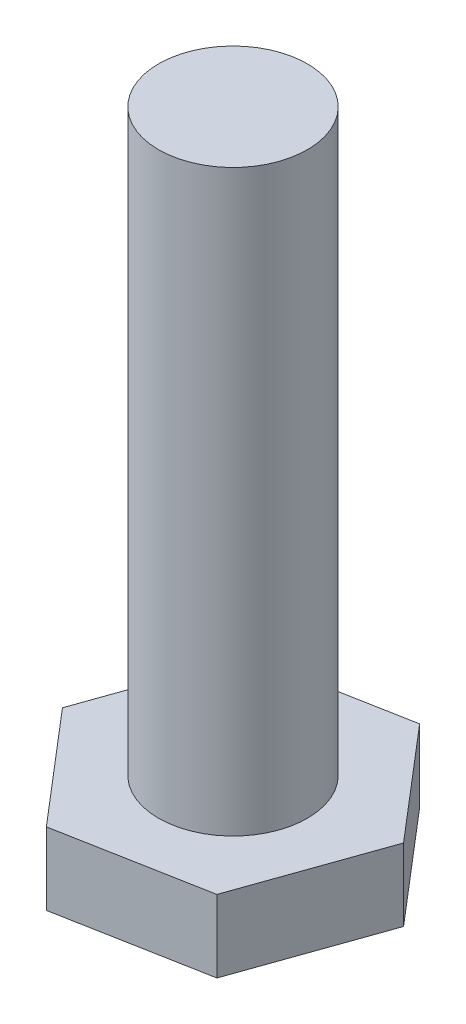
SolidWorks part; units mm, degrees
material "Plain Carbon Steel"
ref_plane "Front Plane" through (0, 0, 0) normal (0, 0, 1) x (1, 0, 0)
ref_plane "Top Plane" through (0, 0, 0) normal (0, 1, 0) x (1, 0, 0)
ref_plane "Right Plane" through (0, 0, 0) normal (1, 0, 0) x (0, 0, -1)
sketch "Sketch1" plane through (0, 0, 0) normal (0, 1, 0) x (1, 0, 0)
  line L1 (2.1374, 6.0493) -> (-4.1701, 4.8757)
  line L2 (-4.1701, 4.8757) -> (-6.3076, -1.1736)
  line L3 (-6.3076, -1.1736) -> (-2.1374, -6.0493)
  line L4 (-2.1374, -6.0493) -> (4.1701, -4.8757)
  line L5 (4.1701, -4.8757) -> (6.3076, 1.1736)
  line L6 (6.3076, 1.1736) -> (2.1374, 6.0493)
  circle A0 centre (0, 0) radius 5.5562 construction
  dimension "D1" = 11.1125
extrude "Boss-Extrude1" add sketch "Sketch1" along normal blind 3.175
sketch "Sketch2" plane through (0, 3.175, 0) normal (0, 1, 0) x (1, 0, 0)
  circle A0 centre (0, 0) radius 3.2639
  dimension "D1" = 6.5278
extrude "Boss-Extrude2" add sketch "Sketch2" along normal blind 25.4
